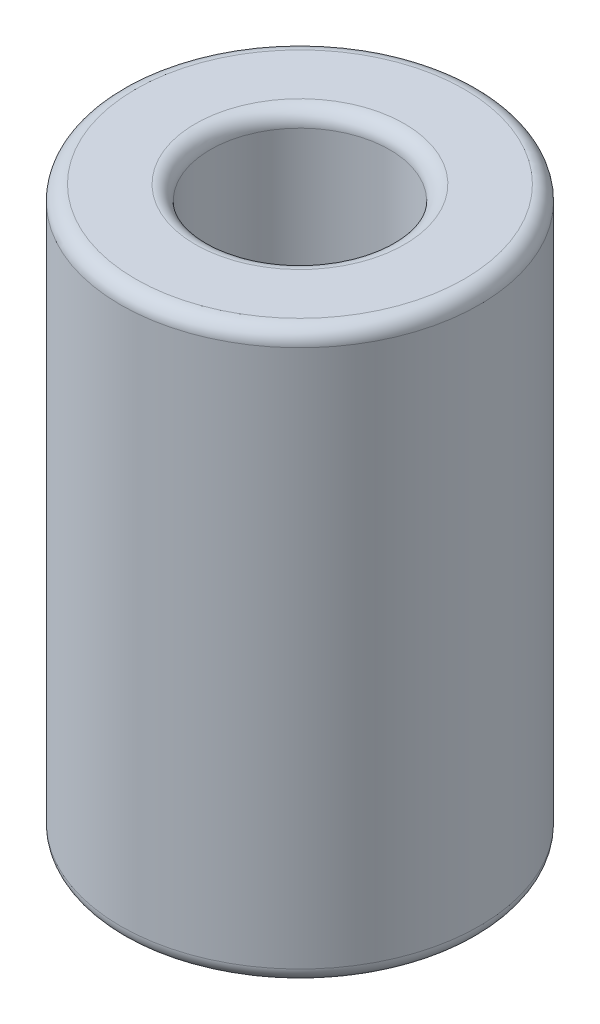
SolidWorks part; units mm, degrees
ref_plane "Front Plane" through (0, 0, 0) normal (0, 0, 1) x (1, 0, 0)
ref_plane "Top Plane" through (0, 0, 0) normal (0, 1, 0) x (1, 0, 0)
ref_plane "Right Plane" through (0, 0, 0) normal (1, 0, 0) x (0, 0, -1)
sketch "Sketch1" plane through (0, 0, 0) normal (0, 1, 0) x (1, 0, 0)
  circle A0 centre (0, 0) radius 3
  circle A1 centre (0, 0) radius 6
  dimension "D1" = 6
  dimension "D2" = 12
extrude "Boss-Extrude1" add sketch "Sketch1" along normal blind 19
fillet "Fillet1" radius 0.5 4 edges at (0, 0, 3) (0, 0, 6) (0, 19, 3) (0, 19, 6)
